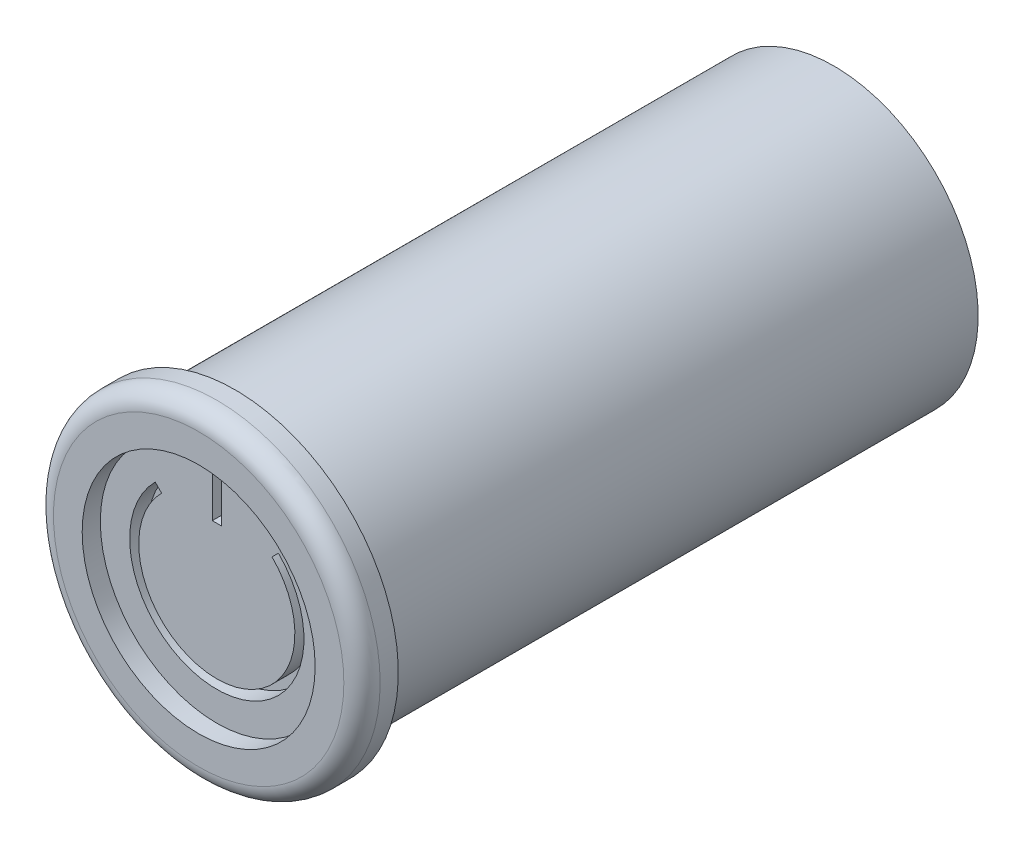
SolidWorks part; units mm, degrees
ref_plane "Front Plane" through (0, 0, 0) normal (0, 0, 1) x (1, 0, 0)
ref_plane "Top Plane" through (0, 0, 0) normal (0, 1, 0) x (1, 0, 0)
ref_plane "Right Plane" through (0, 0, 0) normal (1, 0, 0) x (0, 0, -1)
sketch "Sketch1" plane through (0, 0, 0) normal (0, 0, 1) x (1, 0, 0)
  circle A0 centre (0, 0) radius 9
  dimension "D1" = 18
extrude "Boss-Extrude1" add sketch "Sketch1" along normal blind 35
sketch "Sketch2" plane through (0, 0, 0) normal (0, 0, -1) x (-1, 0, 0)
  circle A0 centre (0, 0) radius 7.95
  circle A1 centre (0, 0) radius 10.727
  dimension "D1" = 15.9
extrude "Cut-Extrude1" cut sketch "Sketch2" against normal blind 33
fillet "Fillet1" radius 1 1 edges at (9, 0, 35)
sketch "Sketch3" plane through (0, 0, 35) normal (0, 0, 1) x (1, 0, 0)
  circle A0 centre (0, 0) radius 6.4186
extrude "Cut-Extrude2" cut sketch "Sketch3" against normal blind 1
sketch "Sketch4" plane through (0, 0, 34) normal (0, 0, 1) x (1, 0, 0)
  line L0 (0, 0) -> (-3.3953, 3.3953) construction
  line L1 (0, 0) -> (3.3953, 3.3953) construction
  line L2 (0, 0) -> (0, 9) construction
  line L3 (-3.3953, 3.3953) -> (-3.0417, 3.0417)
  line L4 (3.0417, 3.0417) -> (3.3953, 3.3953)
  line L6 (-0.25, 5.4792) -> (0.25, 5.4792)
  line L7 (-0.25, 5.4792) -> (-0.25, 3.1248)
  line L8 (-0.25, 3.1248) -> (0.25, 3.1248)
  line L9 (0.25, 5.4792) -> (0.25, 3.1248)
  line L10 (-0.25, 5.4792) -> (0.25, 3.1248) construction
  line L11 (-0.25, 3.1248) -> (0.25, 5.4792) construction
  arc A0 (-3.0417, 3.0417) -> (3.0417, 3.0417) centre (0, 0) ccw
  arc A1 (-3.3953, 3.3953) -> (3.3953, 3.3953) centre (0, 0) ccw
  circle A2 centre (0, 0) radius 9 construction
  circle A4 centre (0, 0) radius 4.3016 construction
  circle A5 centre (0, 0) radius 4.8016 construction
  point P1 (4.8016, 0)
  point P5 (4.1137, 1.2577)
  point P13 (0, 4.302)
  dimension "D2" = 90
  dimension "D3" = 45
  dimension "D4" = 0.5
  dimension "D1" = 0.5
extrude "Cut-Extrude3" cut sketch "Sketch4" against normal blind 1
